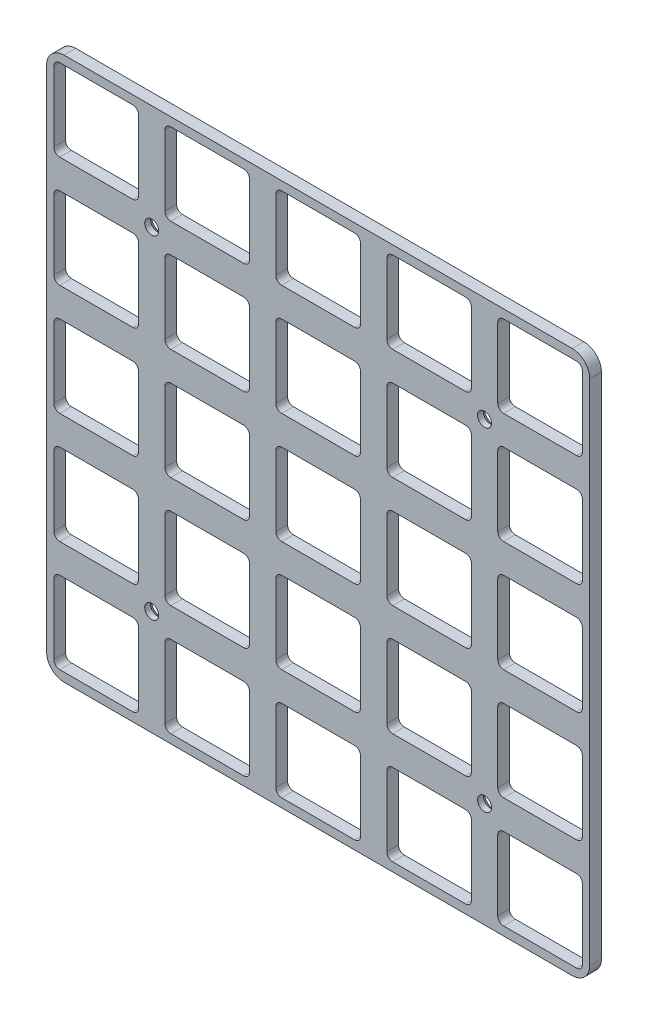
SolidWorks part; units mm, degrees
ref_plane "Front Plane" through (0, 0, 0) normal (0, 0, 1) x (1, 0, 0)
ref_plane "Top Plane" through (0, 0, 0) normal (0, 1, 0) x (1, 0, 0)
ref_plane "Right Plane" through (0, 0, 0) normal (1, 0, 0) x (0, 0, -1)
sketch "Sketch2" plane through (0, 0, 0) normal (0, 0, 1) x (1, 0, 0)
  line L0 (-43.5, 46.5) -> (43.5, 46.5)
  line L1 (-43.5, -47.5) -> (43.5, -47.5) construction
  line L2 (-47.5, -43.5) -> (-47.5, 43.5) construction
  line L3 (-43.5, 47.5) -> (43.5, 47.5) construction
  line L4 (47.5, -43.5) -> (47.5, 43.5) construction
  line L5 (-43.5, -43.5) -> (43.5, 43.5) construction
  line L6 (-43.5, 43.5) -> (43.5, -43.5) construction
  line L7 (46.5, -43.5) -> (46.5, 43.5)
  line L8 (-43.5, -46.5) -> (43.5, -46.5)
  line L9 (-46.5, -43.5) -> (-46.5, 43.5)
  line L10 (-26.25, 44) -> (-26.25, 32)
  line L11 (-44.25, 45) -> (-31.75, 45)
  line L12 (-45.25, 44) -> (-45.25, 32)
  line L13 (-44.25, 31) -> (-31.75, 31)
  line L14 (-30.75, 44) -> (-30.75, 32)
  line L15 (-25.25, 45) -> (-12.75, 45)
  line L16 (-11.75, 44) -> (-11.75, 32)
  line L17 (-25.25, 31) -> (-12.75, 31)
  line L18 (-7.25, 44) -> (-7.25, 32)
  line L19 (-6.25, 45) -> (6.25, 45)
  line L20 (7.25, 44) -> (7.25, 32)
  line L21 (-6.25, 31) -> (6.25, 31)
  line L22 (11.75, 44) -> (11.75, 32)
  line L23 (12.75, 45) -> (25.25, 45)
  line L24 (26.25, 44) -> (26.25, 32)
  line L25 (12.75, 31) -> (25.25, 31)
  line L26 (30.75, 44) -> (30.75, 32)
  line L27 (31.75, 45) -> (44.25, 45)
  line L28 (45.25, 44) -> (45.25, 32)
  line L29 (31.75, 31) -> (44.25, 31)
  line L30 (-26.25, 25) -> (-26.25, 13)
  line L31 (-25.25, 26) -> (-12.75, 26)
  line L32 (-11.75, 25) -> (-11.75, 13)
  line L33 (-25.25, 12) -> (-12.75, 12)
  line L34 (-7.25, 25) -> (-7.25, 13)
  line L35 (-6.25, 26) -> (6.25, 26)
  line L36 (7.25, 25) -> (7.25, 13)
  line L37 (-6.25, 12) -> (6.25, 12)
  line L38 (11.75, 25) -> (11.75, 13)
  line L39 (12.75, 26) -> (25.25, 26)
  line L40 (26.25, 25) -> (26.25, 13)
  line L41 (12.75, 12) -> (25.25, 12)
  line L42 (30.75, 25) -> (30.75, 13)
  line L43 (31.75, 26) -> (44.25, 26)
  line L44 (45.25, 25) -> (45.25, 13)
  line L45 (31.75, 12) -> (44.25, 12)
  line L46 (-26.25, 6) -> (-26.25, -6)
  line L47 (-25.25, 7) -> (-12.75, 7)
  line L48 (-11.75, 6) -> (-11.75, -6)
  line L49 (-25.25, -7) -> (-12.75, -7)
  line L50 (-7.25, 6) -> (-7.25, -6)
  line L51 (-6.25, 7) -> (6.25, 7)
  line L52 (7.25, 6) -> (7.25, -6)
  line L53 (-6.25, -7) -> (6.25, -7)
  line L54 (11.75, 6) -> (11.75, -6)
  line L55 (12.75, 7) -> (25.25, 7)
  line L56 (26.25, 6) -> (26.25, -6)
  line L57 (12.75, -7) -> (25.25, -7)
  line L58 (30.75, 6) -> (30.75, -6)
  line L59 (31.75, 7) -> (44.25, 7)
  line L60 (45.25, 6) -> (45.25, -6)
  line L61 (31.75, -7) -> (44.25, -7)
  line L62 (-26.25, -13) -> (-26.25, -25)
  line L63 (-25.25, -12) -> (-12.75, -12)
  line L64 (-11.75, -13) -> (-11.75, -25)
  line L65 (-25.25, -26) -> (-12.75, -26)
  line L66 (-7.25, -13) -> (-7.25, -25)
  line L67 (-6.25, -12) -> (6.25, -12)
  line L68 (7.25, -13) -> (7.25, -25)
  line L69 (-6.25, -26) -> (6.25, -26)
  line L70 (11.75, -13) -> (11.75, -25)
  line L71 (12.75, -12) -> (25.25, -12)
  line L72 (26.25, -13) -> (26.25, -25)
  line L73 (12.75, -26) -> (25.25, -26)
  line L74 (30.75, -13) -> (30.75, -25)
  line L75 (31.75, -12) -> (44.25, -12)
  line L76 (45.25, -13) -> (45.25, -25)
  line L77 (31.75, -26) -> (44.25, -26)
  line L78 (-26.25, -32) -> (-26.25, -44)
  line L79 (-25.25, -31) -> (-12.75, -31)
  line L80 (-11.75, -32) -> (-11.75, -44)
  line L81 (-25.25, -45) -> (-12.75, -45)
  line L82 (-7.25, -32) -> (-7.25, -44)
  line L83 (-6.25, -31) -> (6.25, -31)
  line L84 (7.25, -32) -> (7.25, -44)
  line L85 (-6.25, -45) -> (6.25, -45)
  line L86 (11.75, -32) -> (11.75, -44)
  line L87 (12.75, -31) -> (25.25, -31)
  line L88 (26.25, -32) -> (26.25, -44)
  line L89 (12.75, -45) -> (25.25, -45)
  line L90 (30.75, -32) -> (30.75, -44)
  line L91 (31.75, -31) -> (44.25, -31)
  line L92 (45.25, -32) -> (45.25, -44)
  line L93 (31.75, -45) -> (44.25, -45)
  line L94 (-45.25, 25) -> (-45.25, 13)
  line L95 (-44.25, 26) -> (-31.75, 26)
  line L96 (-30.75, 25) -> (-30.75, 13)
  line L97 (-44.25, 12) -> (-31.75, 12)
  line L98 (-45.25, 6) -> (-45.25, -6)
  line L99 (-44.25, 7) -> (-31.75, 7)
  line L100 (-30.75, 6) -> (-30.75, -6)
  line L101 (-44.25, -7) -> (-31.75, -7)
  line L102 (-45.25, -13) -> (-45.25, -25)
  line L103 (-44.25, -12) -> (-31.75, -12)
  line L104 (-30.75, -13) -> (-30.75, -25)
  line L105 (-44.25, -26) -> (-31.75, -26)
  line L106 (-45.25, -32) -> (-45.25, -44)
  line L107 (-44.25, -31) -> (-31.75, -31)
  line L108 (-30.75, -32) -> (-30.75, -44)
  line L109 (-44.25, -45) -> (-31.75, -45)
  line L110 (-45.25, 44) -> (-26.25, 44) construction
  line L111 (-45.25, 44) -> (-45.25, 25) construction
  arc A0 (-43.5, -47.5) -> (-47.5, -43.5) centre (-43.5, -43.5) cw construction
  arc A1 (43.5, -47.5) -> (47.5, -43.5) centre (43.5, -43.5) ccw construction
  arc A2 (43.5, 47.5) -> (47.5, 43.5) centre (43.5, 43.5) cw construction
  arc A3 (-47.5, 43.5) -> (-43.5, 47.5) centre (-43.5, 43.5) cw construction
  arc A4 (43.5, 46.5) -> (46.5, 43.5) centre (43.5, 43.5) cw
  arc A5 (43.5, -46.5) -> (46.5, -43.5) centre (43.5, -43.5) ccw
  arc A6 (-43.5, -46.5) -> (-46.5, -43.5) centre (-43.5, -43.5) cw
  arc A7 (-46.5, 43.5) -> (-43.5, 46.5) centre (-43.5, 43.5) cw
  arc A8 (-45.25, 32) -> (-44.25, 31) centre (-44.25, 32) ccw
  arc A9 (-31.75, 31) -> (-30.75, 32) centre (-31.75, 32) ccw
  arc A10 (-31.75, 45) -> (-30.75, 44) centre (-31.75, 44) cw
  arc A11 (-44.25, 45) -> (-45.25, 44) centre (-44.25, 44) ccw
  arc A12 (-25.25, 45) -> (-26.25, 44) centre (-25.25, 44) ccw
  arc A13 (-26.25, 32) -> (-25.25, 31) centre (-25.25, 32) ccw
  arc A14 (-12.75, 45) -> (-11.75, 44) centre (-12.75, 44) cw
  arc A15 (-12.75, 31) -> (-11.75, 32) centre (-12.75, 32) ccw
  arc A16 (-6.25, 45) -> (-7.25, 44) centre (-6.25, 44) ccw
  arc A17 (-7.25, 32) -> (-6.25, 31) centre (-6.25, 32) ccw
  arc A18 (6.25, 45) -> (7.25, 44) centre (6.25, 44) cw
  arc A19 (6.25, 31) -> (7.25, 32) centre (6.25, 32) ccw
  arc A20 (12.75, 45) -> (11.75, 44) centre (12.75, 44) ccw
  arc A21 (11.75, 32) -> (12.75, 31) centre (12.75, 32) ccw
  arc A22 (25.25, 45) -> (26.25, 44) centre (25.25, 44) cw
  arc A23 (25.25, 31) -> (26.25, 32) centre (25.25, 32) ccw
  arc A24 (31.75, 45) -> (30.75, 44) centre (31.75, 44) ccw
  arc A25 (30.75, 32) -> (31.75, 31) centre (31.75, 32) ccw
  arc A26 (44.25, 45) -> (45.25, 44) centre (44.25, 44) cw
  arc A27 (44.25, 31) -> (45.25, 32) centre (44.25, 32) ccw
  arc A28 (-25.25, 26) -> (-26.25, 25) centre (-25.25, 25) ccw
  arc A29 (-26.25, 13) -> (-25.25, 12) centre (-25.25, 13) ccw
  arc A30 (-12.75, 26) -> (-11.75, 25) centre (-12.75, 25) cw
  arc A31 (-12.75, 12) -> (-11.75, 13) centre (-12.75, 13) ccw
  arc A32 (-6.25, 26) -> (-7.25, 25) centre (-6.25, 25) ccw
  arc A33 (-7.25, 13) -> (-6.25, 12) centre (-6.25, 13) ccw
  arc A34 (6.25, 26) -> (7.25, 25) centre (6.25, 25) cw
  arc A35 (6.25, 12) -> (7.25, 13) centre (6.25, 13) ccw
  arc A36 (12.75, 26) -> (11.75, 25) centre (12.75, 25) ccw
  arc A37 (11.75, 13) -> (12.75, 12) centre (12.75, 13) ccw
  arc A38 (25.25, 26) -> (26.25, 25) centre (25.25, 25) cw
  arc A39 (25.25, 12) -> (26.25, 13) centre (25.25, 13) ccw
  arc A40 (31.75, 26) -> (30.75, 25) centre (31.75, 25) ccw
  arc A41 (30.75, 13) -> (31.75, 12) centre (31.75, 13) ccw
  arc A42 (44.25, 26) -> (45.25, 25) centre (44.25, 25) cw
  arc A43 (44.25, 12) -> (45.25, 13) centre (44.25, 13) ccw
  arc A44 (-25.25, 7) -> (-26.25, 6) centre (-25.25, 6) ccw
  arc A45 (-26.25, -6) -> (-25.25, -7) centre (-25.25, -6) ccw
  arc A46 (-12.75, 7) -> (-11.75, 6) centre (-12.75, 6) cw
  arc A47 (-12.75, -7) -> (-11.75, -6) centre (-12.75, -6) ccw
  arc A48 (-6.25, 7) -> (-7.25, 6) centre (-6.25, 6) ccw
  arc A49 (-7.25, -6) -> (-6.25, -7) centre (-6.25, -6) ccw
  arc A50 (6.25, 7) -> (7.25, 6) centre (6.25, 6) cw
  arc A51 (6.25, -7) -> (7.25, -6) centre (6.25, -6) ccw
  arc A52 (12.75, 7) -> (11.75, 6) centre (12.75, 6) ccw
  arc A53 (11.75, -6) -> (12.75, -7) centre (12.75, -6) ccw
  arc A54 (25.25, 7) -> (26.25, 6) centre (25.25, 6) cw
  arc A55 (25.25, -7) -> (26.25, -6) centre (25.25, -6) ccw
  arc A56 (31.75, 7) -> (30.75, 6) centre (31.75, 6) ccw
  arc A57 (30.75, -6) -> (31.75, -7) centre (31.75, -6) ccw
  arc A58 (44.25, 7) -> (45.25, 6) centre (44.25, 6) cw
  arc A59 (44.25, -7) -> (45.25, -6) centre (44.25, -6) ccw
  arc A60 (-25.25, -12) -> (-26.25, -13) centre (-25.25, -13) ccw
  arc A61 (-26.25, -25) -> (-25.25, -26) centre (-25.25, -25) ccw
  arc A62 (-12.75, -12) -> (-11.75, -13) centre (-12.75, -13) cw
  arc A63 (-12.75, -26) -> (-11.75, -25) centre (-12.75, -25) ccw
  arc A64 (-6.25, -12) -> (-7.25, -13) centre (-6.25, -13) ccw
  arc A65 (-7.25, -25) -> (-6.25, -26) centre (-6.25, -25) ccw
  arc A66 (6.25, -12) -> (7.25, -13) centre (6.25, -13) cw
  arc A67 (6.25, -26) -> (7.25, -25) centre (6.25, -25) ccw
  arc A68 (12.75, -12) -> (11.75, -13) centre (12.75, -13) ccw
  arc A69 (11.75, -25) -> (12.75, -26) centre (12.75, -25) ccw
  arc A70 (25.25, -12) -> (26.25, -13) centre (25.25, -13) cw
  arc A71 (25.25, -26) -> (26.25, -25) centre (25.25, -25) ccw
  arc A72 (31.75, -12) -> (30.75, -13) centre (31.75, -13) ccw
  arc A73 (30.75, -25) -> (31.75, -26) centre (31.75, -25) ccw
  arc A74 (44.25, -12) -> (45.25, -13) centre (44.25, -13) cw
  arc A75 (44.25, -26) -> (45.25, -25) centre (44.25, -25) ccw
  arc A76 (-25.25, -31) -> (-26.25, -32) centre (-25.25, -32) ccw
  arc A77 (-26.25, -44) -> (-25.25, -45) centre (-25.25, -44) ccw
  arc A78 (-12.75, -31) -> (-11.75, -32) centre (-12.75, -32) cw
  arc A79 (-12.75, -45) -> (-11.75, -44) centre (-12.75, -44) ccw
  arc A80 (-6.25, -31) -> (-7.25, -32) centre (-6.25, -32) ccw
  arc A81 (-7.25, -44) -> (-6.25, -45) centre (-6.25, -44) ccw
  arc A82 (6.25, -31) -> (7.25, -32) centre (6.25, -32) cw
  arc A83 (6.25, -45) -> (7.25, -44) centre (6.25, -44) ccw
  arc A84 (12.75, -31) -> (11.75, -32) centre (12.75, -32) ccw
  arc A85 (11.75, -44) -> (12.75, -45) centre (12.75, -44) ccw
  arc A86 (25.25, -31) -> (26.25, -32) centre (25.25, -32) cw
  arc A87 (25.25, -45) -> (26.25, -44) centre (25.25, -44) ccw
  arc A88 (31.75, -31) -> (30.75, -32) centre (31.75, -32) ccw
  arc A89 (30.75, -44) -> (31.75, -45) centre (31.75, -44) ccw
  arc A90 (44.25, -31) -> (45.25, -32) centre (44.25, -32) cw
  arc A91 (44.25, -45) -> (45.25, -44) centre (44.25, -44) ccw
  arc A92 (-44.25, 26) -> (-45.25, 25) centre (-44.25, 25) ccw
  arc A93 (-45.25, 13) -> (-44.25, 12) centre (-44.25, 13) ccw
  arc A94 (-31.75, 26) -> (-30.75, 25) centre (-31.75, 25) cw
  arc A95 (-31.75, 12) -> (-30.75, 13) centre (-31.75, 13) ccw
  arc A96 (-44.25, 7) -> (-45.25, 6) centre (-44.25, 6) ccw
  arc A97 (-45.25, -6) -> (-44.25, -7) centre (-44.25, -6) ccw
  arc A98 (-31.75, 7) -> (-30.75, 6) centre (-31.75, 6) cw
  arc A99 (-31.75, -7) -> (-30.75, -6) centre (-31.75, -6) ccw
  arc A100 (-44.25, -12) -> (-45.25, -13) centre (-44.25, -13) ccw
  arc A101 (-45.25, -25) -> (-44.25, -26) centre (-44.25, -25) ccw
  arc A102 (-31.75, -12) -> (-30.75, -13) centre (-31.75, -13) cw
  arc A103 (-31.75, -26) -> (-30.75, -25) centre (-31.75, -25) ccw
  arc A104 (-44.25, -31) -> (-45.25, -32) centre (-44.25, -32) ccw
  arc A105 (-45.25, -44) -> (-44.25, -45) centre (-44.25, -44) ccw
  arc A106 (-31.75, -31) -> (-30.75, -32) centre (-31.75, -32) cw
  arc A107 (-31.75, -45) -> (-30.75, -44) centre (-31.75, -44) ccw
  point P0 (0, 0)
  dimension "D1" = 4
  dimension "D4" = 1
  dimension "D2" = 95
  dimension "D5" = 14.5
  dimension "D6" = 2.25
  dimension "D9" = 90
  dimension "D10" = 19
  dimension "D11" = 19
  dimension "D12" = 2.25
  dimension "D13" = 14
  dimension "D14" = 2.5
  dimension "D3" = 1
  dimension "D7" = 5
  dimension "D8" = 5
extrude "Boss-Extrude1" add sketch "Sketch2" along normal blind 2
sketch "Sketch3" plane through (0, 0, 0) normal (0, 0, -1) x (-1, 0, 0)
  line L0 (43.5, 43.5) -> (-43.5, -43.5) construction
  line L1 (43.5, 43.5) -> (-43.5, -43.5) construction
  point P2 (-28.5, -28.5)
  point P32 (-28.5, 28.5)
  point P34 (28.5, 28.5)
  point P36 (28.5, -28.5)
  dimension "D1" = 28.5
  dimension "D2" = 57
  dimension "D3" = 4
  dimension "D4" = 40.3051
hole_wizard "CSK for M2 Flat Head Machine Screw1" positions "Sketch3" profile "Sketch7" countersink size "M2" standard "ANSI Metric" end condition through all
sketch "Sketch7" plane through (-28.5, -28.5, 0) normal (1, 0, 0) x (0, 1, 0)
  line L0 (0, 0) -> (0, 2)
  line L1 (0, 2) -> (1.2, 2)
  line L2 (1.2, 2) -> (1.2, 1)
  line L3 (1.2, 1) -> (2.2, 0)
  line L5 (2.2, 0) -> (0, 0)
  line L6 (-1.2, 1) -> (-2.2, 0) construction
  line L11 (0, -6.35) -> (0, 107.95) construction
  dimension "Thru Hole Dia." = 2.4
  dimension "Thru Hole Depth" = 2
  dimension "Near C'Sink Dia." = 4.4
  dimension "Near C'Sink Angle" = 90
